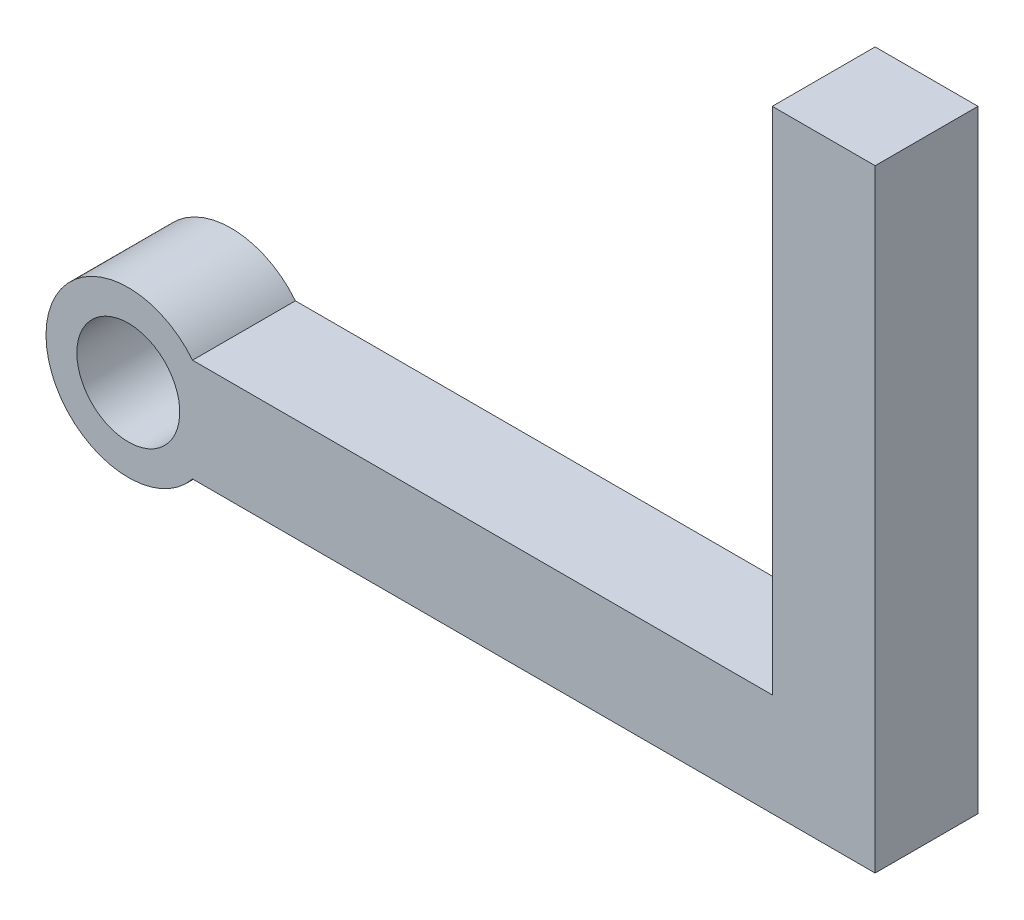
SolidWorks part; units mm, degrees
ref_plane "Front Plane" through (0, 0, 0) normal (0, 0, 1) x (1, 0, 0)
ref_plane "Top Plane" through (0, 0, 0) normal (0, 1, 0) x (1, 0, 0)
ref_plane "Right Plane" through (0, 0, 0) normal (1, 0, 0) x (0, 0, -1)
sketch "Sketch1" plane through (0, 0, 0) normal (0, 1, 0) x (1, 0, 0)
  line L5 (-42.926, 44.45) -> (-42.926, 31.75) construction
  line L6 (-42.926, -44.45) -> (42.926, -44.45)
  line L11 (-42.926, -44.45) -> (-42.926, 44.45)
  line L12 (-42.926, 44.45) -> (42.926, 44.45)
  line L13 (42.926, -44.45) -> (42.926, 44.45)
  line L14 (-42.926, -44.45) -> (42.926, 44.45) construction
  line L16 (-42.926, 44.45) -> (42.926, -44.45) construction
  line L18 (-42.926, 31.75) -> (42.926, 31.75)
  line L19 (-42.926, 31.75) -> (-42.926, 44.45)
  line L20 (-42.926, 44.45) -> (42.926, 44.45)
  line L34 (42.926, 31.75) -> (42.926, 44.45)
  line L35 (-42.926, 31.75) -> (42.926, 44.45) construction
  line L36 (-42.926, 44.45) -> (42.926, 31.75) construction
  point P0 (0, 0)
  point P12 (0, 38.1)
  dimension "D1" = 88.9
  dimension "D2" = 85.852
  dimension "D3" = 12.7
extrude "Boss-Extrude1" add sketch "Sketch1" along normal blind 12.7 contours L11 L18 L13 L12
sketch "Sketch9" plane through (0, 12.7, 0) normal (0, 1, 0) x (1, 0, 0)
  line L0 (42.926, 38.1) -> (36.576, 38.1) construction
  line L1 (42.926, 31.75) -> (42.926, 44.45) construction
  line L4 (30.226, 31.75) -> (42.926, 31.75)
  line L5 (30.226, 31.75) -> (30.226, 44.45)
  line L6 (30.226, 44.45) -> (42.926, 44.45)
  line L7 (42.926, 31.75) -> (42.926, 44.45)
  line L8 (30.226, 31.75) -> (42.926, 44.45) construction
  line L9 (30.226, 44.45) -> (42.926, 31.75) construction
  dimension "D1" = 6.35
extrude "Boss-Extrude2" add sketch "Sketch9" along normal blind 62.9331
ref_plane "Plane5" through (0, 0, -44.45) normal (0, 0, -1) x (-1, 0, 0)
sketch "Sketch10" plane through (0, 0, -44.45) normal (0, 0, -1) x (-1, 0, 0)
  line L0 (42.926, 0) -> (49.276, 0)
  line L1 (49.276, 0) -> (49.276, 6.35)
  circle A0 centre (49.276, 6.35) radius 10.16
  dimension "D2" = 6.35
  dimension "D3" = 20.32
  dimension "D1" = 6.35
extrude "Boss-Extrude3" add sketch "Sketch10" against normal blind 12.7
hole_wizard "1/2 (0.5) Diameter Hole1" positions "3DSketch3" profile "Sketch13" hole size "1/2" standard "ANSI Inch" end condition through all
sketch3d "3DSketch3"
  line L0 (-59.436, 6.35, -44.45) -> (-49.276, 6.35, -44.45) construction
  line L2 (-49.276, 6.35, -31.75) -> (-49.276, 6.35, -44.45) construction
  arc A1 (-41.3449, 0, -44.45) -> (-41.3449, 12.7, -44.45) centre (-49.276, 6.35, -44.45) ccw construction
  point P2 (-49.276, 6.35, -44.45)
  point P12 (-49.276, 6.35, -54.61)
  dimension "D1" = 10.16
sketch "Sketch13" plane through (-49.276, 6.35, -44.45) normal (1, 0, 0) x (0, 1, 0)
  line L0 (0, 0) -> (0, 12.7)
  line L1 (0, 12.7) -> (6.35, 12.7)
  line L2 (6.35, 12.7) -> (6.35, 0)
  line L5 (6.35, 0) -> (0, 0)
  line L11 (0, -6.35) -> (0, 107.95) construction
  dimension "Thru Hole Dia." = 12.7
  dimension "Thru Hole Depth" = 12.7
